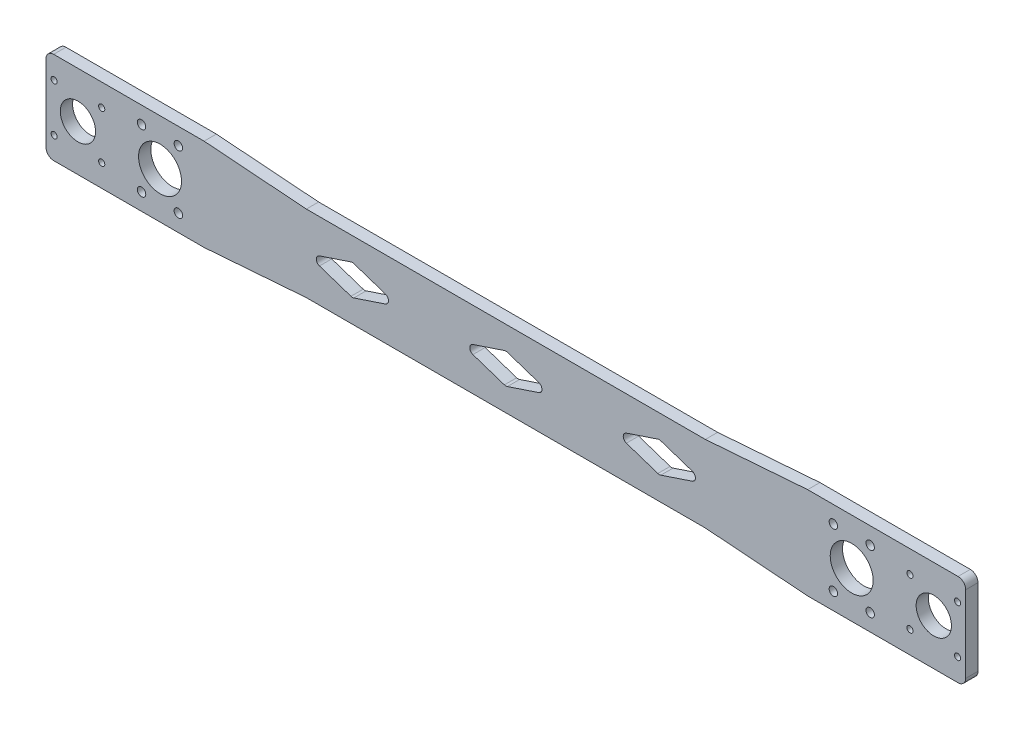
SolidWorks part; units mm, degrees
ref_plane "前视基准面" through (0, 0, 0) normal (0, 0, 1) x (1, 0, 0)
ref_plane "上视基准面" through (0, 0, 0) normal (0, 1, 0) x (1, 0, 0)
ref_plane "右视基准面" through (0, 0, 0) normal (1, 0, 0) x (0, 0, -1)
other "Configuration Table"
sketch "草图1" plane through (0, 0, 0) normal (0, 0, 1) x (1, 0, 0)
  line L0 (299.65, 5) -> (299.65, -55) construction
  line L1 (0, 0) -> (103, 0)
  line L2 (0, 0) -> (0, -60)
  line L3 (0, -60) -> (103, -60)
  line L4 (599.3, 0) -> (599.3, -60)
  line L5 (103, 0) -> (169.65, -5)
  line L6 (169.65, -5) -> (429.65, -5)
  line L7 (429.65, -5) -> (496.3, 0)
  line L8 (496.3, 0) -> (599.3, 0)
  line L9 (0, -30) -> (599.3, -30) construction
  line L10 (429.65, -55) -> (496.3, -60)
  line L11 (169.65, -55) -> (429.65, -55)
  line L12 (103, -60) -> (169.65, -55)
  line L13 (496.3, -60) -> (599.3, -60)
  line L14 (169.65, -30) -> (199.65, -20)
  line L15 (169.65, -30) -> (199.65, -40)
  line L16 (199.65, -20) -> (229.65, -30)
  line L17 (199.65, -40) -> (229.65, -30)
  line L18 (269.65, -30) -> (299.65, -20)
  line L19 (269.65, -30) -> (299.65, -40)
  line L20 (299.65, -40) -> (329.65, -30)
  line L21 (299.65, -20) -> (329.65, -30)
  line L22 (369.65, -30) -> (399.65, -20)
  line L23 (369.65, -30) -> (399.65, -40)
  line L24 (399.65, -40) -> (429.65, -30)
  line L25 (399.65, -20) -> (429.65, -30)
  dimension "D1" = 60
  dimension "D2" = 599.3
  dimension "D3" = 103
  dimension "D4" = 66.65
  dimension "D5" = 260
  dimension "D6" = 130
  dimension "D7" = 5
  dimension "D8" = 103
  dimension "D9" = 70
  dimension "D10" = 30
  dimension "D11" = 20
  dimension "D12" = 3
extrude "凸台-拉伸1" add sketch "草图1" along normal blind 8
fillet "圆角1" radius 3 12 edges at (199.65, -40, 4) (229.65, -30, 4) (169.65, -30, 4) (199.65, -20, 4) (369.65, -30, 4) (399.65, -20, 4) (429.65, -30, 4) (399.65, -40, 4) (299.65, -40, 4) (329.65, -30, 4) (269.65, -30, 4) (299.65, -20, 4)
fillet "圆角2" radius 5 4 edges at (599.3, -60, 4) (599.3, 0, 4) (0, -60, 4) (0, 0, 4)
sketch "草图2" plane through (0, 0, 8) normal (0, 0, 1) x (1, 0, 0)
  line L0 (0, -30) -> (74.4257, -30) construction
  line L1 (0, -5) -> (0, -55) construction
  line L2 (299.65, -5) -> (299.65, -55) construction
  line L3 (429.65, -5) -> (169.65, -5) construction
  line L4 (169.65, -55) -> (429.65, -55) construction
  circle A0 centre (74.3, -30) radius 14
  circle A1 centre (525, -30) radius 14
  dimension "D1" = 28
  dimension "D2" = 74.3
extrude "切除-拉伸1" cut sketch "草图2" against normal blind 10
sketch "草图3" plane through (0, 0, 0) normal (0, 0, -1) x (-1, 0, 0)
  line L0 (-299.65, -5) -> (-299.65, -55) construction
  line L1 (-429.65, -5) -> (-169.65, -5) construction
  line L2 (-169.65, -55) -> (-429.65, -55) construction
  circle A0 centre (-537.05, -11) radius 2.75
  circle A1 centre (-513.05, -11) radius 2.75
  circle A2 centre (-513.05, -49) radius 2.75
  circle A3 centre (-537.05, -49) radius 2.75
  circle A4 centre (-62.25, -49) radius 2.75
  circle A5 centre (-86.25, -49) radius 2.75
  circle A6 centre (-86.25, -11) radius 2.75
  circle A7 centre (-62.25, -11) radius 2.75
  dimension "D1" = 5.5
  dimension "D2" = 2
  dimension "D3" = 2
extrude "切除-拉伸2" cut sketch "草图3" against normal blind 10
sketch "草图4" plane through (0, 0, 8) normal (0, 0, 1) x (1, 0, 0)
  line L0 (74.3, -30) -> (18.8753, -30) construction
  line L1 (299.65, -5) -> (299.65, -55) construction
  line L2 (429.65, -5) -> (169.65, -5) construction
  line L3 (169.65, -55) -> (429.65, -55) construction
  circle A0 centre (20.8, -30) radius 11.5
  circle A1 centre (5.3, -14.5) radius 2
  circle A2 centre (36.3, -14.5) radius 2
  circle A3 centre (36.3, -45.5) radius 2
  circle A4 centre (5.3, -45.5) radius 2
  circle A5 centre (563, -45.5) radius 2
  circle A6 centre (594, -45.5) radius 2
  circle A7 centre (594, -14.5) radius 2
  circle A8 centre (563, -14.5) radius 2
  circle A9 centre (578.5, -30) radius 11.5
  dimension "D1" = 23
  dimension "D5" = 4
  dimension "D2" = 53.5
  dimension "D3" = 15.5
  dimension "D4" = 15.5
  dimension "D6" = 2
  dimension "D7" = 2
extrude "切除-拉伸3" cut sketch "草图4" against normal blind 10
